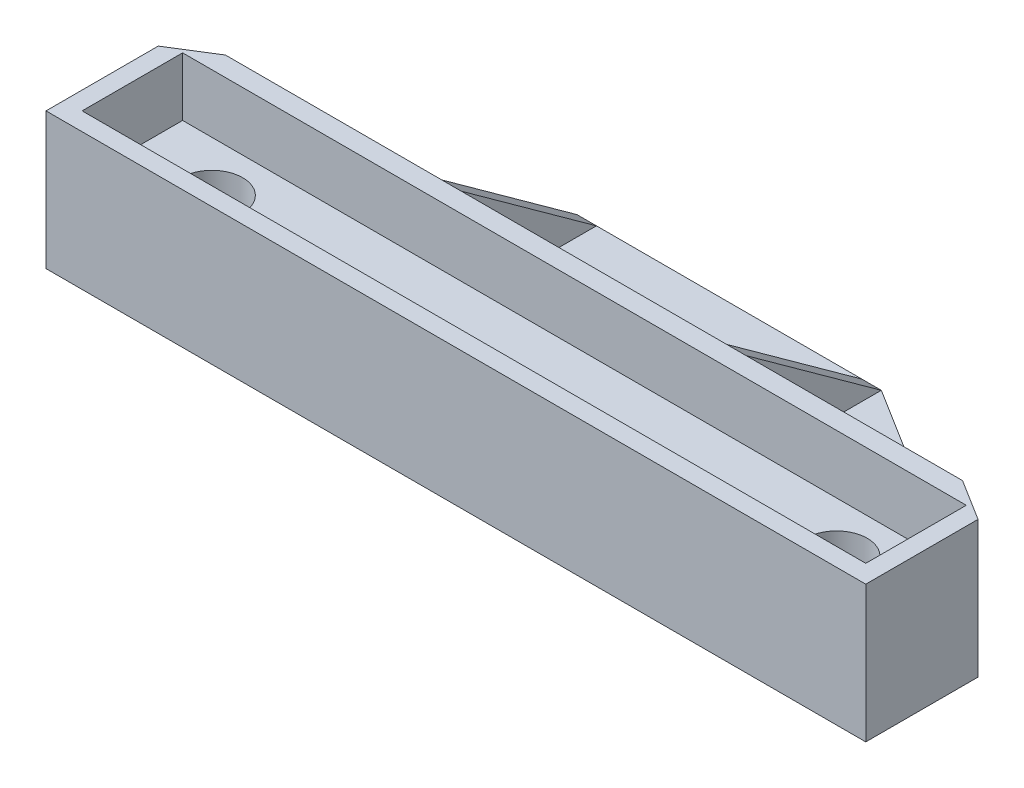
SolidWorks part; units mm, degrees
ref_plane "Front Plane" through (0, 0, 0) normal (0, 0, 1) x (1, 0, 0)
ref_plane "Top Plane" through (0, 0, 0) normal (0, 1, 0) x (1, 0, 0)
ref_plane "Right Plane" through (0, 0, 0) normal (1, 0, 0) x (0, 0, -1)
sketch "Sketch1" plane through (0, 0, 0) normal (0, 1, 0) x (1, 0, 0)
  line L0 (0, 0) -> (0, 13.8356) construction
  line L1 (-18.9996, 7) -> (18.9996, 7)
  line L2 (-21, 5.75) -> (-21, 0)
  line L3 (-21, 0) -> (21, 0)
  line L4 (21, 5.75) -> (21, 0)
  line L5 (21, 5.75) -> (18.9996, 7)
  line L6 (-21, 5.75) -> (-18.9996, 7)
  point P0 (0, 0)
  dimension "D1" = 32
  dimension "D2" = 42
  dimension "D3" = 7
  dimension "D4" = 5.75
extrude "Riser" add sketch "Sketch1" along normal blind 7
sketch "Sketch2" plane through (0, 0, 0) normal (0, -1, 0) x (1, 0, 0)
  line L1 (0, 0) -> (0, -7) construction
  line L2 (-21, 0) -> (21, 0) construction
  line L4 (18.9996, -7) -> (-18.9996, -7) construction
  line L5 (21, 0) -> (21, -5.75) construction
  circle A0 centre (16, -3.5) radius 1.575
  circle A2 centre (-16, -3.5) radius 1.575
  point P2 (0, 0)
  point P5 (0, 0)
  point P11 (0, 0)
  point P12 (0, -3.5)
  dimension "D2" = 3.15
  dimension "D1" = 5
extrude "Mounting Holes" cut sketch "Sketch2" against normal through all
sketch "Sketch3" plane through (0, 7, 0) normal (0, 1, 0) x (1, 0, 0)
  line L5 (18.9996, 7) -> (-18.9996, 7) construction
  line L12 (-20.075, 6.075) -> (20.075, 6.075)
  line L13 (-20.075, 6.075) -> (-20.075, 0.925)
  line L14 (-20.075, 0.925) -> (20.075, 0.925)
  line L15 (20.075, 6.075) -> (20.075, 0.925)
  line L16 (21, 0) -> (21, 5.75) construction
  dimension "D1" = 5.15
  dimension "D2" = 40.15
  dimension "D3" = 0.925
  dimension "D4" = 0.925
extrude "Recess" cut sketch "Sketch3" against normal blind 3 contours L12 L15 L14 L13
sketch "Sketch4" plane through (0, 0, 0) normal (0, 1, 0) x (1, 0, 0)
  line L0 (-28.0926, 1.318) -> (7.8348, 23.768) construction
  line L1 (-18.9996, 7) -> (18.9996, 7)
  line L3 (7.7972, 14) -> (-7.7972, 14)
  line L4 (-7.7972, 14) -> (-18.9996, 7)
  line L5 (0, 0) -> (0, 16.9853) construction
  line L6 (7.7972, 14) -> (18.9996, 7)
  dimension "D1" = 32
  dimension "D2" = 7
extrude "Flange" add sketch "Sketch4" along normal blind 7
sketch "Sketch5" plane through (0, 7, 0) normal (0, 1, 0) x (1, 0, 0)
  line L0 (-6.7972, 7.075) -> (-6.7972, 14)
  line L1 (7.7972, 14) -> (-7.7972, 14) construction
  line L2 (-6.7972, 14) -> (6.7972, 14)
  line L3 (6.7972, 14) -> (6.7972, 7.075)
  line L4 (6.7972, 7.075) -> (-6.7972, 7.075)
  line L5 (-18.8796, 7.075) -> (-7.7972, 7.075)
  line L8 (-7.7972, 14) -> (-21, 5.75) construction
  line L9 (-7.7972, 7.075) -> (-7.7972, 14)
  line L10 (-7.7972, 14) -> (-18.8796, 7.075)
  line L11 (0, 0) -> (0, 24.5183) construction
  line L12 (7.7972, 7.075) -> (7.7972, 14)
  line L13 (18.8796, 7.075) -> (7.7972, 7.075)
  line L14 (7.7972, 14) -> (18.8796, 7.075)
  line L15 (-20.075, 6.075) -> (20.075, 6.075) construction
  dimension "D1" = 1
  dimension "D2" = 1
  dimension "D4" = 1
extrude "Flange Cutout" cut sketch "Sketch5" against normal blind 5
sketch "Sketch7" plane through (6.7972, 0, 0) normal (-1, 0, 0) x (0, 0, 1)
  line L0 (-7.075, 7) -> (-14, 2)
  line L1 (-14, 2) -> (-14, 7)
  line L2 (-14, 7) -> (-7.075, 7)
extrude "Angle Cutout" cut sketch "Sketch7" against normal through all and the other way through all
chamfer "Flange Chamfer" distance 1 angle 45 3 edges at (0, 2, -7.075) (13.3384, 2, -7.075) (-13.3384, 2, -7.075)
